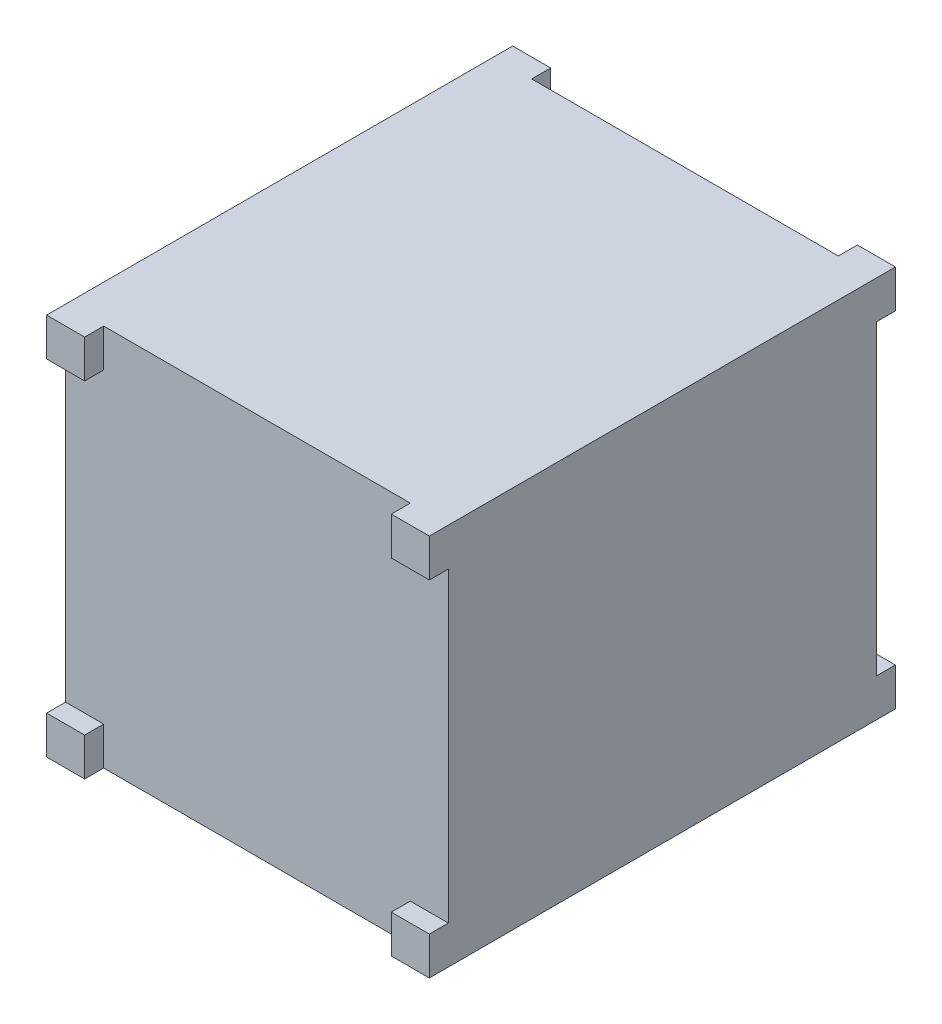
SolidWorks part; units mm, degrees
ref_plane "Front Plane" through (0, 0, 0) normal (0, 0, 1) x (1, 0, 0)
ref_plane "Top Plane" through (0, 0, 0) normal (0, 1, 0) x (1, 0, 0)
ref_plane "Right Plane" through (0, 0, 0) normal (1, 0, 0) x (0, 0, -1)
sketch "Sketch1" plane through (0, 0, 0) normal (0, 0, 1) x (1, 0, 0)
  line L1 (50.3, -50.3) -> (-50.3, -50.3)
  line L2 (50.3, -50.3) -> (50.3, 50.3)
  line L3 (50.3, 50.3) -> (-50.3, 50.3)
  line L4 (-50.3, -50.3) -> (-50.3, 50.3)
  line L5 (50.3, -50.3) -> (-50.3, 50.3) construction
  line L6 (50.3, 50.3) -> (-50.3, -50.3) construction
  point P0 (0, 0)
  dimension "D1" = 100.6
  dimension "D2" = 100.6
extrude "Boss-Extrude1" add sketch "Sketch1" along normal mid plane 112.5
sketch "Sketch2" plane through (0, 0, 56.25) normal (0, 0, 1) x (1, 0, 0)
  line L0 (0, 50.3) -> (0, -50.3) construction
  line L1 (-50.3, 50.3) -> (-40.3, 50.3)
  line L2 (-50.3, 50.3) -> (-50.3, 40.3)
  line L3 (-50.3, 40.3) -> (-40.3, 40.3)
  line L4 (-40.3, 50.3) -> (-40.3, 40.3)
  line L5 (50.3, 50.3) -> (-50.3, 50.3) construction
  line L6 (-50.3, -50.3) -> (50.3, -50.3) construction
  line L7 (50.3, 40.3) -> (40.3, 40.3)
  line L8 (40.3, 50.3) -> (40.3, 40.3)
  line L9 (50.3, 50.3) -> (40.3, 50.3)
  line L10 (50.3, 50.3) -> (50.3, 40.3)
  line L11 (-50.3, 0) -> (50.3, 0) construction
  line L12 (-50.3, 50.3) -> (-50.3, -50.3) construction
  line L13 (50.3, -50.3) -> (50.3, 50.3) construction
  line L14 (50.3, -50.3) -> (50.3, -40.3)
  line L15 (50.3, -50.3) -> (40.3, -50.3)
  line L16 (40.3, -50.3) -> (40.3, -40.3)
  line L17 (50.3, -40.3) -> (40.3, -40.3)
  line L18 (-50.3, -40.3) -> (-40.3, -40.3)
  line L19 (-40.3, -50.3) -> (-40.3, -40.3)
  line L20 (-50.3, -50.3) -> (-40.3, -50.3)
  line L21 (-50.3, -50.3) -> (-50.3, -40.3)
  dimension "D1" = 10
  dimension "D2" = 10
extrude "Boss-Extrude2" add sketch "Sketch2" along normal blind 5
sketch "Sketch3" plane through (0, 0, -56.25) normal (0, 0, -1) x (-1, 0, 0)
  line L0 (0, 50.3) -> (0, 0) construction
  line L1 (-50.3, 50.3) -> (-40.3, 50.3)
  line L2 (-50.3, 50.3) -> (-50.3, 40.3)
  line L3 (-50.3, 40.3) -> (-40.3, 40.3)
  line L4 (-40.3, 50.3) -> (-40.3, 40.3)
  line L5 (-50.3, 50.3) -> (50.3, 50.3) construction
  line L6 (0, 0) -> (50.3, 0) construction
  line L7 (50.3, 50.3) -> (50.3, -50.3) construction
  line L8 (50.3, 40.3) -> (40.3, 40.3)
  line L9 (40.3, 50.3) -> (40.3, 40.3)
  line L10 (50.3, 50.3) -> (40.3, 50.3)
  line L11 (50.3, 50.3) -> (50.3, 40.3)
  line L12 (50.3, -50.3) -> (50.3, -40.3)
  line L13 (50.3, -50.3) -> (40.3, -50.3)
  line L14 (40.3, -50.3) -> (40.3, -40.3)
  line L15 (50.3, -40.3) -> (40.3, -40.3)
  line L16 (-50.3, -40.3) -> (-40.3, -40.3)
  line L17 (-40.3, -50.3) -> (-40.3, -40.3)
  line L18 (-50.3, -50.3) -> (-40.3, -50.3)
  line L19 (-50.3, -50.3) -> (-50.3, -40.3)
  dimension "D1" = 10
  dimension "D2" = 10
extrude "Boss-Extrude3" add sketch "Sketch3" along normal blind 5
